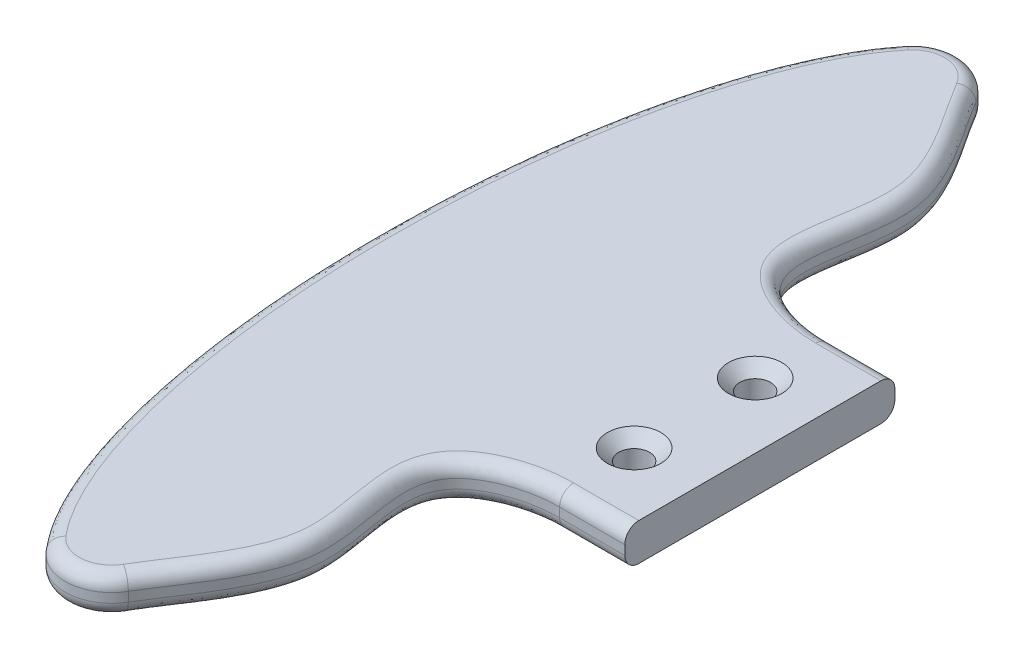
SolidWorks part; units mm, degrees
ref_plane "Ebene vorne" through (0, 0, 0) normal (0, 0, 1) x (1, 0, 0)
ref_plane "Ebene oben" through (0, 0, 0) normal (0, 1, 0) x (1, 0, 0)
ref_plane "Ebene rechts" through (0, 0, 0) normal (1, 0, 0) x (0, 0, -1)
sketch "Sketch1" plane through (0, 0, 0) normal (0, 1, 0) x (1, 0, 0)
  line L0 (19.5662, 0) -> (23.748, 0) construction
  line L1 (16.748, -14.5) -> (23.748, -14.5)
  line L3 (16.748, 14.5) -> (23.748, 14.5)
  line L4 (23.748, -14.5) -> (23.748, 14.5)
  line L5 (17.5, 0) -> (9.7386, 0) construction
  ellipse E0 centre (0, 0) end of major axis (0, -50) minor radius 17.5 (16.748, 14.5) -> (16.748, -14.5) ccw
  dimension "D1" = 100
  dimension "D2" = 35
  dimension "D3" = 29
  dimension "D4" = 7
extrude "Boss-Extrude1" add sketch "Sketch1" along normal blind 4
sketch "Sketch2" plane through (0, 4, 0) normal (0, 1, 0) x (1, 0, 0)
  line L0 (16.748, -14.5) -> (23.748, -14.5) construction
  line L1 (23.748, 14.5) -> (9.748, 14.5)
  line L2 (23.748, 14.5) -> (23.748, -14.5)
  line L3 (23.748, -14.5) -> (9.748, -14.5)
  line L4 (9.748, 14.5) -> (9.748, -14.5)
  dimension "D1" = 14
extrude "Spacer" [suppressed] add sketch "Sketch2" along normal blind 5
sketch "Sketch4" [suppressed] plane through (0, 0, -14.5) normal (0, 0, -1) x (-1, 0, 0)
  line L0 (-25.2924, 9) -> (-39.2924, 3.9044)
  line L2 (-39.2924, 3.9044) -> (-39.2924, 9)
  line L3 (-39.2924, 9) -> (-25.2924, 9)
  dimension "D1" = 70
extrude "Angle" [suppressed] cut sketch "Sketch4" against normal up to surface (29 mm away)
sketch "Sketch6" [suppressed] plane through (5.8512, 16.076, 0) normal (0.342, 0.9397, 0) x (0.9397, -0.342, 0)
  line L0 (28.0874, 6.5) -> (28.0874, -6.5) construction
  line L1 (35.5874, -14.5) -> (35.5874, 14.5) construction
  line L2 (35.5874, 0) -> (20.6889, 0) construction
  line L3 (20.6889, 14.5) -> (20.6889, -14.5) construction
  line L4 (28.0874, 0) -> (51.5252, 0) construction
  circle A0 centre (28.0874, 6.5) radius 1.65
  circle A1 centre (28.0874, -6.5) radius 1.65
  dimension "D1" = 3.3
  dimension "D2" = 13
  dimension "D3" = 7.5
extrude "Cut-Extrude1" [suppressed] cut sketch "Sketch6" against normal through all
sketch "Sketch7" plane through (0, 4, 0) normal (0, 1, 0) x (1, 0, 0)
  line L0 (0, 50) -> (0, 12.0004) construction
  line L1 (-17.5, 0) -> (-3.5208, 0) construction
  line L2 (23.748, 14.5) -> (16.748, 14.5) construction
  line L3 (0, -50) -> (0, -15.7144) construction
  line L4 (16.748, -14.5) -> (23.748, -14.5) construction
  ellipse E0 centre (0, 0) end of major axis (0, -50) minor radius 17.5 (16.748, 14.5) -> (16.748, -14.5) ccw construction
  spline S0 degree 3 poles (49.1735, 54.3857) (31.4165, 30.0315) (25.324, 10.6786) (3.5407, 17.7194) (12.8718, 34.7187) (-16.8788, 59.681) (49.1735, 54.3857) (31.4165, 30.0315) (25.324, 10.6786) knots -0.570845 -0.412801 -0.081397 0 0.232925 0.31026 0.429155 0.587199 0.918603 1 1.232925 1.31026 1.429155 only from (35.8352, 35.5) to (35.8352, 35.5)
  spline S1 degree 3 poles (29.7911, -30.8223) (25.2302, -10.6282) (3.4958, -17.7543) (12.9121, -34.6884) (-17.0602, -59.8136) (50.5401, -53.6674) (29.7911, -30.8223) (25.2302, -10.6282) (3.4958, -17.7543) knots -0.645145 -0.313197 -0.227978 0 0.077463 0.196552 0.354855 0.686803 0.772022 1 1.077463 1.196552 1.354855 only from (16.748, -14.5) to (16.748, -14.5)
  dimension "D3" = 20
  dimension "D1" = 8
  dimension "D2" = 8
  dimension "D4" = 40
  dimension "D5" = 21
  dimension "D6" = 30
  dimension "D7" = 21
  dimension "D8" = 32
  dimension "D9" = 40
  dimension "D10" = 30
  dimension "D11" = 32
  dimension "D12" = 8
  dimension "D13" = 8
  dimension "D14" = 20
extrude "Cut-Extrude3" cut sketch "Sketch7" against normal blind 10
fillet "Fillet1" radius 5 5 edges at (-17.5, 0, 0) (-17.5, 4, 0) (0, 2, -50)
fillet "Fillet2" radius 5 1 edges at (0, 2, 50)
fillet "Fillet4" radius 1.5 7 edges at (20.248, 4, -14.5) (-17.5, 4, -0.0201) (-2.4423, 4, -47.9579) (-2.4568, 4, 47.9473) (20.248, 4, 14.5)
fillet "Fillet5" radius 1.5 7 edges at (-17.5, 0, -0.0201) (-2.4423, 0, -47.9579) (-2.4568, 0, 47.9473) (20.248, 0, -14.5) (20.248, 0, 14.5)
sketch "Sketch8" plane through (0, 4, 0) normal (0, 1, 0) x (1, 0, 0)
  line L0 (23.748, 0) -> (10.7021, 0) construction
  line L1 (23.748, -13) -> (23.748, 13) construction
  line L2 (16.748, -6.5) -> (16.748, 6.5) construction
  line L3 (16.748, 0) -> (25.6639, 0) construction
  circle A0 centre (16.748, -6.5) radius 1.65
  circle A1 centre (16.748, 6.5) radius 1.65
  spline S0 degree 3 poles (-5.5412, 45.2377) (-6.1879, 44.4738) (-6.7576, 43.6641) (-7.8041, 41.9892) (-8.2794, 41.1233) (-9.162, 39.3509) (-9.5698, 38.4414) (-10.3238, 36.6102) (-10.6708, 35.6871) (-11.6406, 32.9001) (-12.1931, 31.0186) (-13.1637, 27.222) (-13.581, 25.3067) (-14.306, 21.4488) (-14.6136, 19.5061) (-15.0032, 16.5742) (-15.1211, 15.5936) (-15.333, 13.6362) (-15.4273, 12.658) (-15.843, 7.7702) (-16.0007, 3.869) (-15.9993, -3.9173) (-15.8402, -7.8022) (-15.1809, -15.5547) (-14.6829, -19.4223) (-13.6017, -25.2065) (-13.185, -27.1317) (-12.206, -30.9746) (-11.6488, -32.8749) (-10.6742, -35.6783) (-10.3259, -36.6049) (-9.571, -38.4388) (-9.1646, -39.3451) (-8.2846, -41.1136) (-7.8105, -41.9779) (-6.7668, -43.6505) (-6.1984, -44.4596) (-5.5531, -45.2236) knots 0 0 0 0 0.03125 0.03125 0.0625 0.0625 0.09375 0.09375 0.125 0.125 0.1875 0.1875 0.25 0.25 0.3125 0.3125 0.34375 0.34375 0.375 0.375 0.5 0.5 0.625 0.625 0.75 0.75 0.8125 0.8125 0.875 0.875 0.90625 0.90625 0.9375 0.9375 0.96875 0.96875 1 1 1 1 construction
  point P10 (-16, -0.0241)
  dimension "D1" = 3.3
  dimension "D2" = 32.748
  dimension "D3" = 13
extrude "M3 Screws no Angle" cut sketch "Sketch8" against normal through all
sketch "Sketch9" plane through (0, 4, 0) normal (0, 1, 0) x (1, 0, 0)
  circle A0 centre (16.748, 6.5) radius 2.875
  circle A1 centre (16.748, -6.5) radius 2.875
  dimension "D1" = 5.75
extrude "M3 Head" cut sketch "Sketch9" against normal blind 10 draft 45
